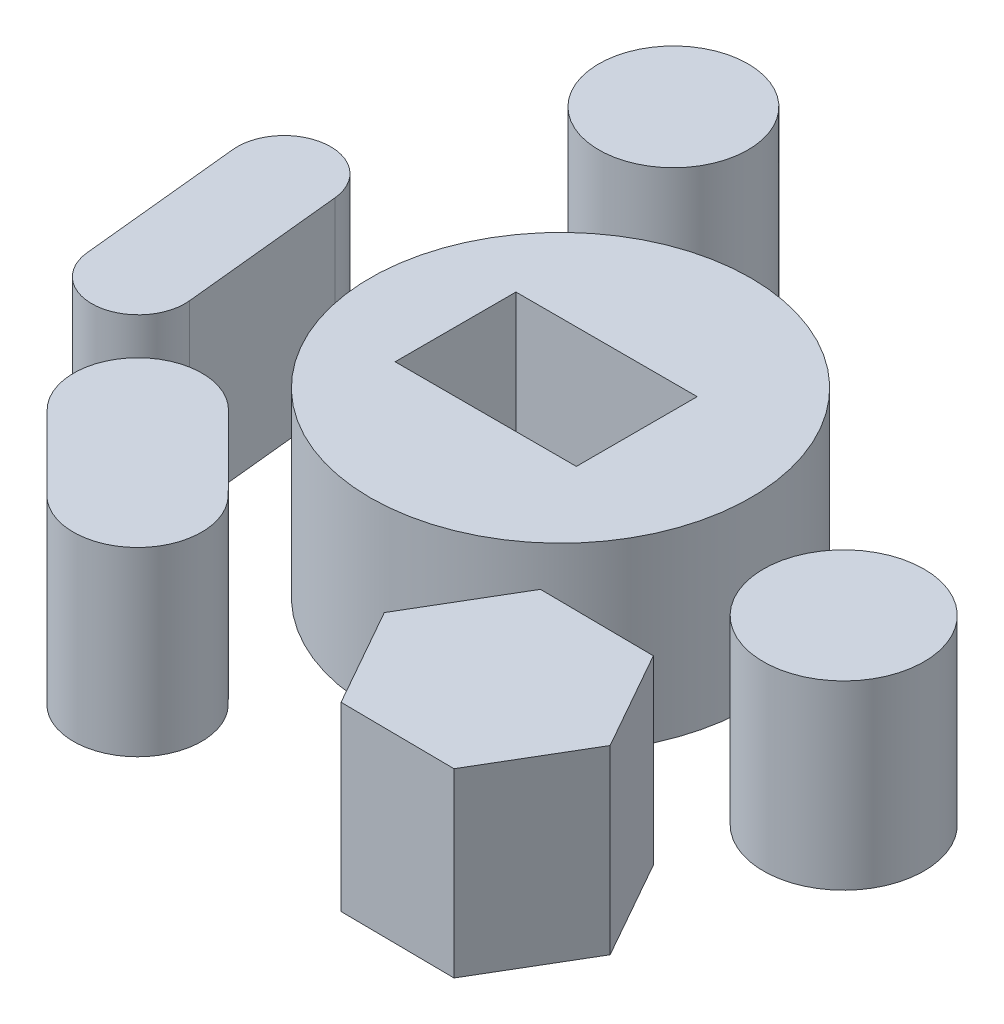
SolidWorks part; units mm, degrees
ref_plane "Front Plane" through (0, 0, 0) normal (0, 0, 1) x (1, 0, 0)
ref_plane "Top Plane" through (0, 0, 0) normal (0, 1, 0) x (1, 0, 0)
ref_plane "Right Plane" through (0, 0, 0) normal (1, 0, 0) x (0, 0, -1)
sketch "Sketch1" plane through (0, 0, 0) normal (0, 1, 0) x (1, 0, 0)
  line L0 (-183.7469, 90.3135) -> (-169.9051, -46.0269) construction
  line L1 (0, 0) -> (152.4, 0)
  line L2 (0, 0) -> (0, 101.6)
  line L3 (0, 101.6) -> (152.4, 101.6)
  line L4 (152.4, 0) -> (152.4, 101.6)
  line L5 (225.2265, -270.6605) -> (321.0882, -271.5805)
  line L6 (321.0882, -271.5805) -> (369.8158, -189.0218)
  line L7 (369.8158, -189.0218) -> (322.6817, -105.5431)
  line L8 (322.6817, -105.5431) -> (226.82, -104.6231)
  line L9 (226.82, -104.6231) -> (178.0924, -187.1818)
  line L10 (178.0924, -187.1818) -> (225.2265, -270.6605)
  line L11 (-144.7158, 94.2761) -> (-130.8739, -42.0642)
  line L12 (-222.778, 86.3509) -> (-208.9362, -49.9895)
  line L13 (-11.1846, -205.4234) -> (-72.9666, -143.3782) construction
  line L14 (-49.4047, -243.4814) -> (-111.1867, -181.4362)
  line L15 (27.0355, -167.3655) -> (-34.7466, -105.3203)
  circle A0 centre (88.5054, 50.5784) radius 160.0544
  circle A1 centre (373.2899, 3.911) radius 67.5466
  circle A2 centre (273.9541, -188.1018) radius 83.0225 construction
  circle A3 centre (-68.6385, 302.6432) radius 62.7284
  arc A4 (-144.7158, 94.2761) -> (-222.778, 86.3509) centre (-183.7469, 90.3135) ccw
  arc A5 (-208.9362, -49.9895) -> (-130.8739, -42.0642) centre (-169.9051, -46.0269) ccw
  arc A6 (-49.4047, -243.4814) -> (27.0355, -167.3655) centre (-11.1846, -205.4234) ccw
  arc A7 (-34.7466, -105.3203) -> (-111.1867, -181.4362) centre (-72.9666, -143.3782) ccw
  point P21 (-176.826, 22.1433)
  point P26 (-42.0756, -174.4008)
  dimension "D1" = 152.4
  dimension "D2" = 101.6
extrude "Boss-Extrude1" add sketch "Sketch1" along normal blind 152.4
